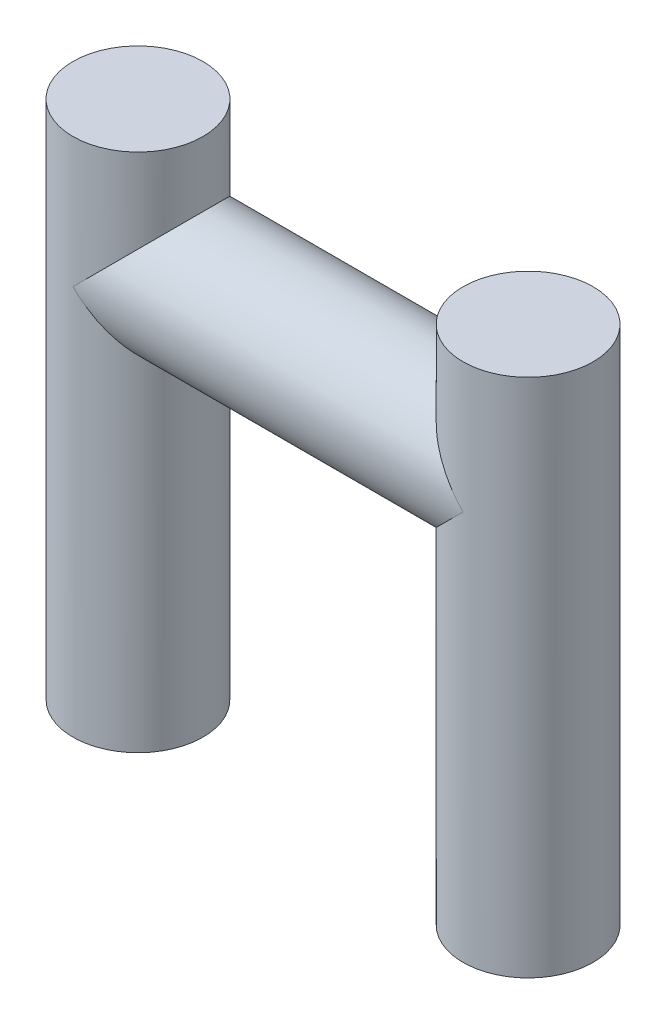
SolidWorks part; units mm, degrees
ref_plane "Front Plane" through (0, 0, 0) normal (0, 0, 1) x (1, 0, 0)
ref_plane "Top Plane" through (0, 0, 0) normal (0, 1, 0) x (1, 0, 0)
ref_plane "Right Plane" through (0, 0, 0) normal (1, 0, 0) x (0, 0, -1)
sketch "Sketch2" plane through (0, 0, 0) normal (0, 1, 0) x (1, 0, 0)
  circle A0 centre (0, 0) radius 2.5
  dimension "D1" = 5
extrude "Boss-Extrude2" add sketch "Sketch2" along normal blind 10
sketch "Sketch3" plane through (0, 0, 0) normal (1, 0, 0) x (0, 0, -1)
  line L0 (0, 0) -> (0, 10) construction
  line L1 (2.5, 10) -> (-2.5, 10) construction
  line L2 (-2.5, 5) -> (2.5, 5) construction
  line L3 (-2.5, 10) -> (-2.5, 0) construction
  line L4 (2.5, 0) -> (2.5, 10) construction
  circle A0 centre (0, 5) radius 2.5
  dimension "D1" = 5
extrude "Boss-Extrude3" add sketch "Sketch3" along normal blind 7.5
mirror "Mirror5" about plane through (7.5, 5, 0) normal (1, 0, 0) of "Boss-Extrude2", "Boss-Extrude3"
sketch "Sketch4" plane through (0, 0, 0) normal (0, -1, 0) x (-1, 0, 0)
  circle A0 centre (0, 0) radius 2.5
  circle A1 centre (-15, 0) radius 2.5
extrude "Boss-Extrude4" add sketch "Sketch4" along normal blind 10
